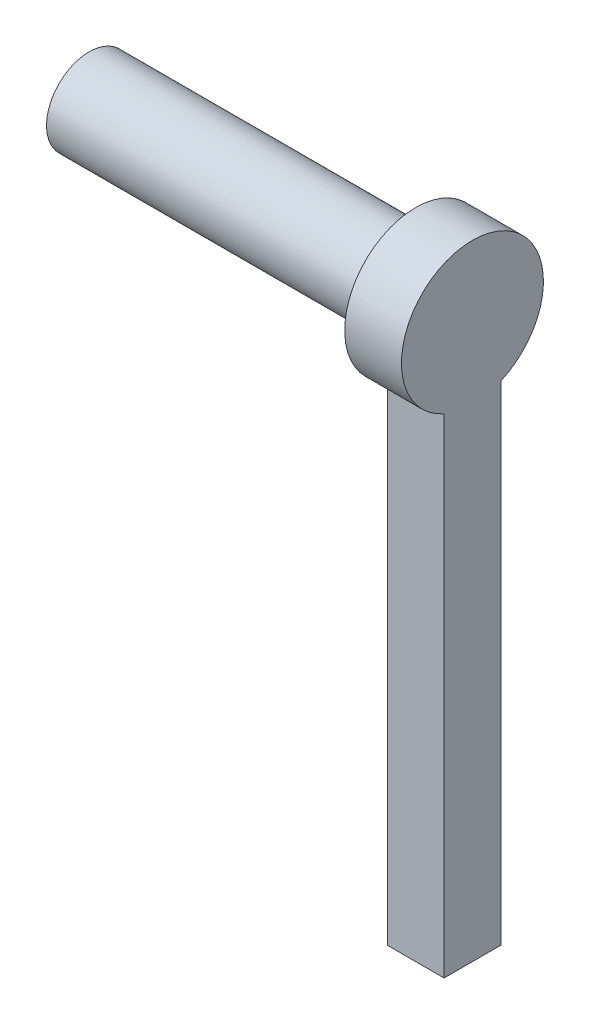
SolidWorks part; units mm, degrees
other "Preload Manual Lock Pin"
ref_plane "Front Plane" through (0, 0, 0) normal (0, 0, 1) x (1, 0, 0)
ref_plane "Top Plane" through (0, 0, 0) normal (0, 1, 0) x (1, 0, 0)
ref_plane "Right Plane" through (0, 0, 0) normal (1, 0, 0) x (0, 0, -1)
sketch3d "Service pin shank sketch datum points"
  point P0 (-12, -29, -10.5)
  point P1 (-12, -19, -10.5)
  point P2 (-12, -29, -0.5)
ref_plane "Service pin shank sketch plane" through (-12, 0, 0) normal (1, 0, 0) x (0, 0, -1)
sketch "Service pin shank sketch" plane through (-12, 0, 0) normal (1, 0, 0) x (0, 0, -1)
  circle A0 centre (10.5, -29) radius 1.5
extrude "Service pin shank" add sketch "Service pin shank sketch" along normal blind 11.5 separate body
sketch3d "Service pin head sketch datum points"
  point P0 (-0.5, -29, -10.5)
  point P1 (-0.5, -19, -10.5)
  point P2 (-0.5, -29, -0.5)
ref_plane "Service pin head sketch plane" through (-0.5, 0, 0) normal (1, 0, 0) x (0, 0, -1)
sketch "Service pin head sketch" plane through (-0.5, 0, 0) normal (1, 0, 0) x (0, 0, -1)
  circle A0 centre (10.5, -29) radius 2.5
extrude "Service pin head" add sketch "Service pin head sketch" along normal blind 2
sketch3d "Lock switch flag sketch datum points"
  point P0 (-0.5, -48.5, -11.5)
  point P1 (9.5, -48.5, -11.5)
  point P2 (-0.5, -38.5, -11.5)
ref_plane "Lock switch flag sketch plane" through (0, 0, -11.5) normal (0, 0, 1) x (1, 0, 0)
sketch "Lock switch flag sketch" plane through (0, 0, -11.5) normal (0, 0, 1) x (1, 0, 0)
  line L0 (-0.5, -48.5) -> (1.5, -48.5)
  line L1 (1.5, -48.5) -> (1.5, -29)
  line L2 (1.5, -29) -> (-0.5, -29)
  line L3 (-0.5, -29) -> (-0.5, -48.5)
extrude "Lock switch flag" add sketch "Lock switch flag sketch" along normal blind 2
